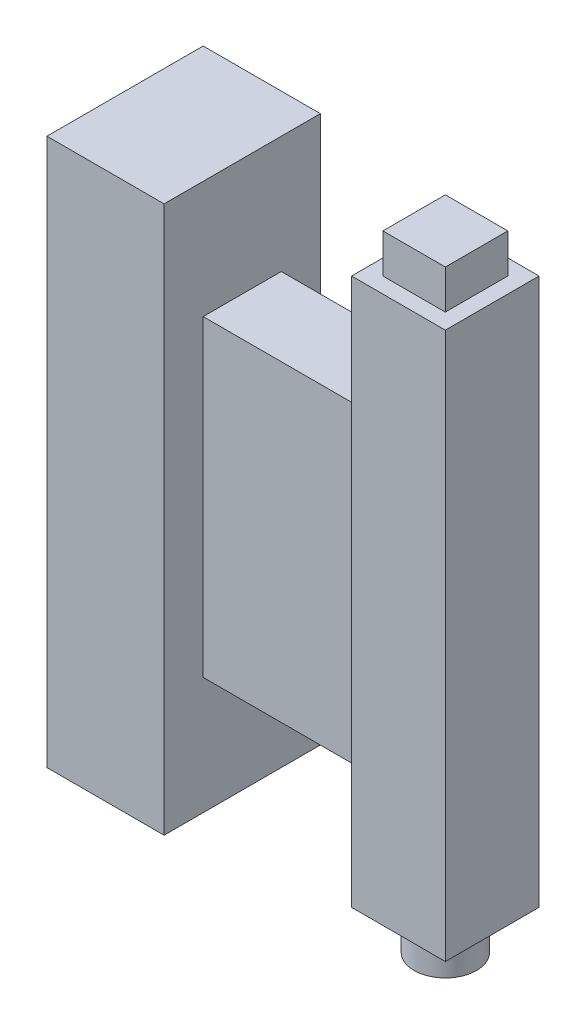
SolidWorks part; units mm, degrees
ref_plane "Front Plane" through (0, 0, 0) normal (0, 0, 1) x (1, 0, 0)
ref_plane "Top Plane" through (0, 0, 0) normal (0, 1, 0) x (1, 0, 0)
ref_plane "Right Plane" through (0, 0, 0) normal (1, 0, 0) x (0, 0, -1)
sketch "Sketch1" plane through (0, 0, 0) normal (0, 0, 1) x (1, 0, 0)
  line L1 (7.5, 35) -> (-7.5, 35)
  line L2 (7.5, 35) -> (7.5, -35)
  line L3 (7.5, -35) -> (-7.5, -35)
  line L4 (-7.5, 35) -> (-7.5, -35)
  line L5 (7.5, 35) -> (-7.5, -35) construction
  line L6 (7.5, -35) -> (-7.5, 35) construction
  point P0 (0, 0)
  dimension "D1" = 15
  dimension "D3" = 70
extrude "Boss-Extrude1" add sketch "Sketch1" along normal mid plane 20
sketch "Sketch2" plane through (0, 0, 0) normal (0, 0, 1) x (1, 0, 0)
  line L0 (7.5, 20) -> (27.5, 20)
  line L1 (7.5, -35) -> (7.5, 35) construction
  line L4 (7.5, -20) -> (27.5, -20)
  line L9 (7.5, -20) -> (7.5, 20)
  line L10 (27.5, 20) -> (27.5, -20)
  point P15 (7.5, 0)
  dimension "D1" = 40
  dimension "D2" = 20
extrude "Boss-Extrude2" add sketch "Sketch2" along normal mid plane 10
sketch "Sketch5" plane through (0, 0, 0) normal (0, 0, 1) x (1, 0, 0)
  line L0 (27.5, -20) -> (27.5, 20) construction
  line L1 (39.5, -35) -> (27.5, -35)
  line L2 (39.5, -35) -> (39.5, 35)
  line L3 (39.5, 35) -> (27.5, 35)
  line L4 (27.5, -35) -> (27.5, 35)
  line L5 (39.5, -35) -> (27.5, 35) construction
  line L6 (39.5, 35) -> (27.5, -35) construction
  line L7 (7.5, 35) -> (-7.5, 35) construction
  line L8 (-7.5, -35) -> (7.5, -35) construction
  point P0 (33.5, 0)
  dimension "D1" = 12
extrude "Boss-Extrude4" add sketch "Sketch5" along normal mid plane 12
sketch "Sketch6" plane through (0, 35, 0) normal (0, 1, 0) x (1, 0, 0)
  line L0 (27.5, -6) -> (27.5, 6) construction
  line L1 (37.5, -4) -> (29.5, -4)
  line L2 (37.5, -4) -> (37.5, 4)
  line L3 (37.5, 4) -> (29.5, 4)
  line L4 (29.5, -4) -> (29.5, 4)
  line L5 (37.5, -4) -> (29.5, 4) construction
  line L6 (37.5, 4) -> (29.5, -4) construction
  line L7 (39.5, 6) -> (27.5, 6) construction
  point P0 (33.5, 0)
  dimension "D1" = 6
  dimension "D2" = 6
  dimension "D3" = 8
  dimension "D4" = 8
extrude "Boss-Extrude5" add sketch "Sketch6" along normal blind 5
sketch "Sketch7" plane through (0, -35, 0) normal (0, -1, 0) x (1, 0, 0)
  line L0 (27.5, 6) -> (27.5, -6) construction
  line L1 (27.5, 6) -> (39.5, 6) construction
  circle A0 centre (33.5, 0) radius 4
  dimension "D1" = 8
  dimension "D3" = 6
  dimension "D2" = 6
extrude "Boss-Extrude6" add sketch "Sketch7" along normal blind 5
sketch "Sketch8" plane through (-7.5, 0, 0) normal (-1, 0, 0) x (0, 0, 1)
  line L0 (0, 27) -> (0, 9) construction
  line L1 (0, 9) -> (0, -9) construction
  line L2 (0, -9) -> (0, -27) construction
  line L3 (10, -35) -> (-10, -35) construction
  circle A0 centre (0, 27) radius 5
  circle A1 centre (0, 9) radius 5
  circle A2 centre (0, -9) radius 5
  circle A3 centre (0, -27) radius 5
  point P8 (0, 0)
  dimension "D1" = 10
  dimension "D2" = 8
extrude "Cut-Extrude1" cut sketch "Sketch8" against normal blind 5
sketch "Sketch9" plane through (0, -35, 0) normal (0, -1, 0) x (1, 0, 0)
  line L0 (-7.5, -10) -> (-7.5, 10)
  line L2 (-7.5, 10) -> (-7.5, -10) construction
  circle A0 centre (-44, 0) radius 36.5
  point P3 (-7.5, 0)
  dimension "D2" = 73
  dimension "D1" = 20
